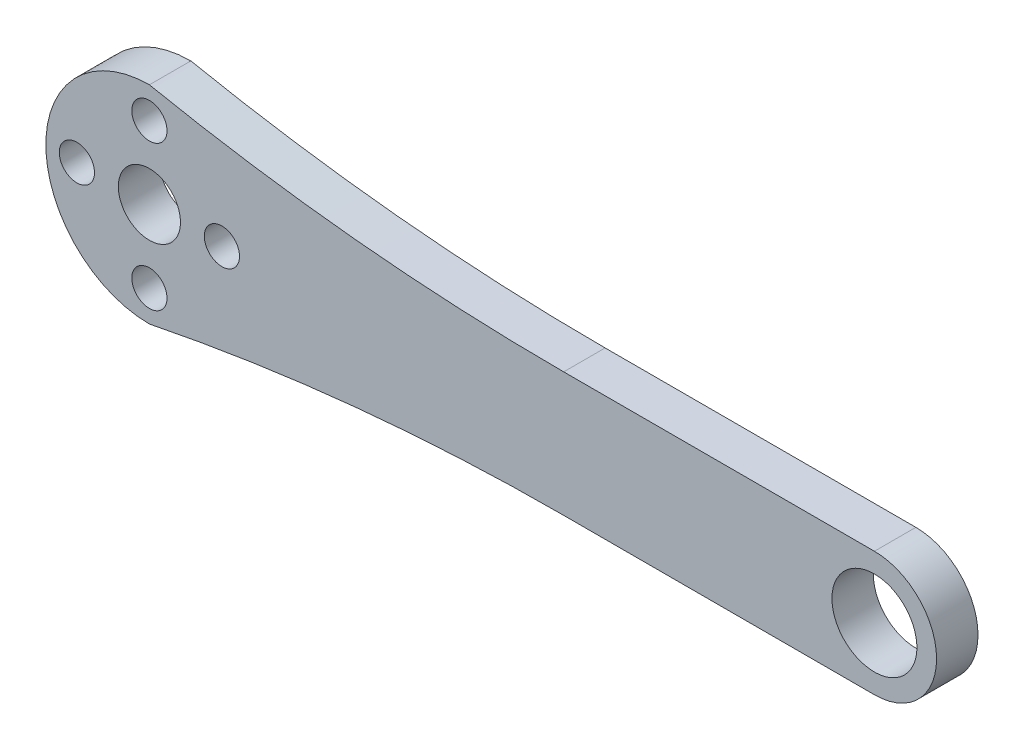
SolidWorks part; units mm, degrees
ref_plane "前视基准面" through (0, 0, 0) normal (0, 0, 1) x (1, 0, 0)
ref_plane "上视基准面" through (0, 0, 0) normal (0, 1, 0) x (1, 0, 0)
ref_plane "右视基准面" through (0, 0, 0) normal (1, 0, 0) x (0, 0, -1)
other "Configuration Table"
ref_plane "基准面1" through (0, 0, 4) normal (0, 0, 1) x (1, 0, 0)
sketch "草图1" plane through (0, 0, 4) normal (0, 0, 1) x (1, 0, 0)
  line L0 (40, -6) -> (70, -6)
  line L1 (70, 6) -> (40, 6)
  circle A0 centre (0, 7) radius 1.7
  circle A1 centre (0, 0) radius 3
  circle A2 centre (-7, 0) radius 1.7
  circle A3 centre (0, -7) radius 1.7
  circle A4 centre (7, 0) radius 1.7
  arc A5 (40, 6) -> (0, 10) centre (40, 208) cw
  arc A6 (0, 10) -> (0, -10) centre (0, 0) ccw
  arc A7 (0, -10) -> (40, -6) centre (40, -208) cw
  arc A8 (70, -6) -> (70, 6) centre (70, 0) ccw
  circle A9 centre (70, 0) radius 4.1
  dimension "D1" = 6
  dimension "D2" = 3.4
  dimension "D3" = 3.4
  dimension "D4" = 3.4
  dimension "D5" = 3.4
  dimension "D6" = 10
  dimension "D7" = 8.2
  dimension "D8" = 70
extrude "凸台-拉伸1" add sketch "草图1" against normal blind 4
